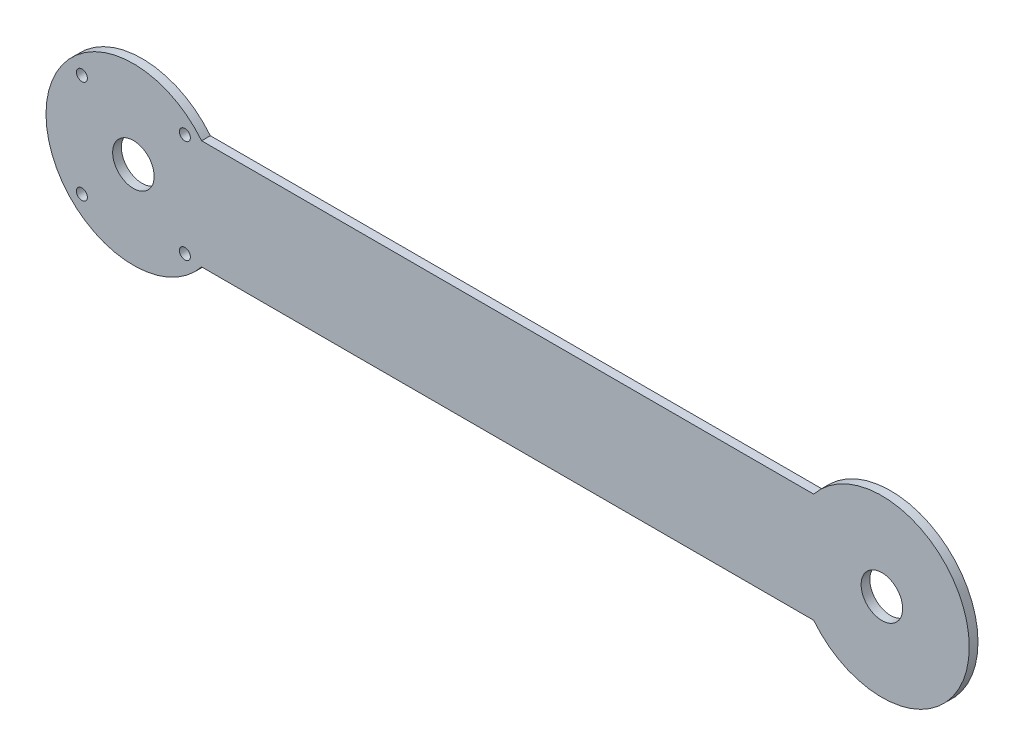
SolidWorks part; units mm, degrees
ref_plane "前视基准面" through (0, 0, 0) normal (0, 0, 1) x (1, 0, 0)
ref_plane "上视基准面" through (0, 0, 0) normal (0, 1, 0) x (1, 0, 0)
ref_plane "右视基准面" through (0, 0, 0) normal (1, 0, 0) x (0, 0, -1)
sketch "草图1" plane through (0, 0, 0) normal (0, 0, 1) x (1, 0, 0)
  line L0 (0, 0) -> (342.5662, 0) construction
  line L1 (31.225, 25) -> (311.3412, 25)
  line L2 (31.225, -25) -> (311.3412, -25)
  circle A0 centre (-23.57, 23.57) radius 2.5
  circle A1 centre (23.57, 23.57) radius 2.5
  circle A2 centre (23.57, -23.57) radius 2.5
  circle A3 centre (-23.57, -23.57) radius 2.5
  circle A4 centre (0, 0) radius 40 construction
  circle A5 centre (342.5662, 0) radius 40 construction
  arc A6 (31.225, 25) -> (31.225, -25) centre (0, 0) ccw
  arc A7 (311.3412, 25) -> (311.3412, -25) centre (342.5662, 0) cw
  circle A8 centre (342.5662, 0) radius 9.5
  circle A9 centre (0, 0) radius 9.5
  dimension "D1" = 5
  dimension "D5" = 80
  dimension "D7" = 19
  dimension "D8" = 19
  dimension "D2" = 23.57
  dimension "D3" = 23.57
  dimension "D6" = 25
  dimension "D4" = 4
extrude "凸台-拉伸1" add sketch "草图1" along normal blind 4 contours L2 A7 L1 A6
